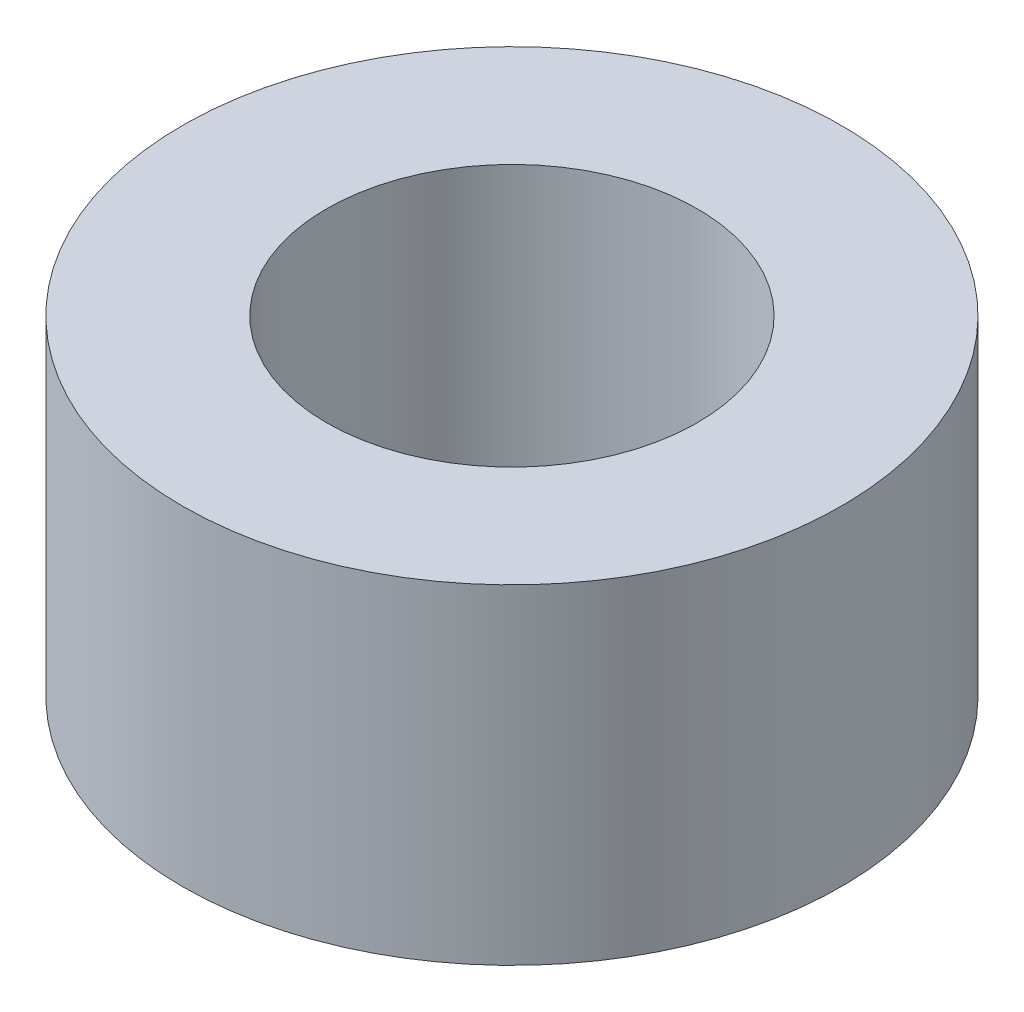
SolidWorks part; units mm, degrees
ref_plane "Спереди" through (0, 0, 0) normal (0, 0, 1) x (1, 0, 0)
ref_plane "Сверху" through (0, 0, 0) normal (0, 1, 0) x (1, 0, 0)
ref_plane "Справа" through (0, 0, 0) normal (1, 0, 0) x (0, 0, -1)
sketch "Эскиз1" plane through (0, 0, 0) normal (0, 1, 0) x (1, 0, 0)
  circle A0 centre (0, 0) radius 4
  circle A1 centre (0, 0) radius 2.25
  dimension "D1" = 4.5
  dimension "D2" = 8
extrude "Бобышка-Вытянуть1" add sketch "Эскиз1" along normal blind 4
